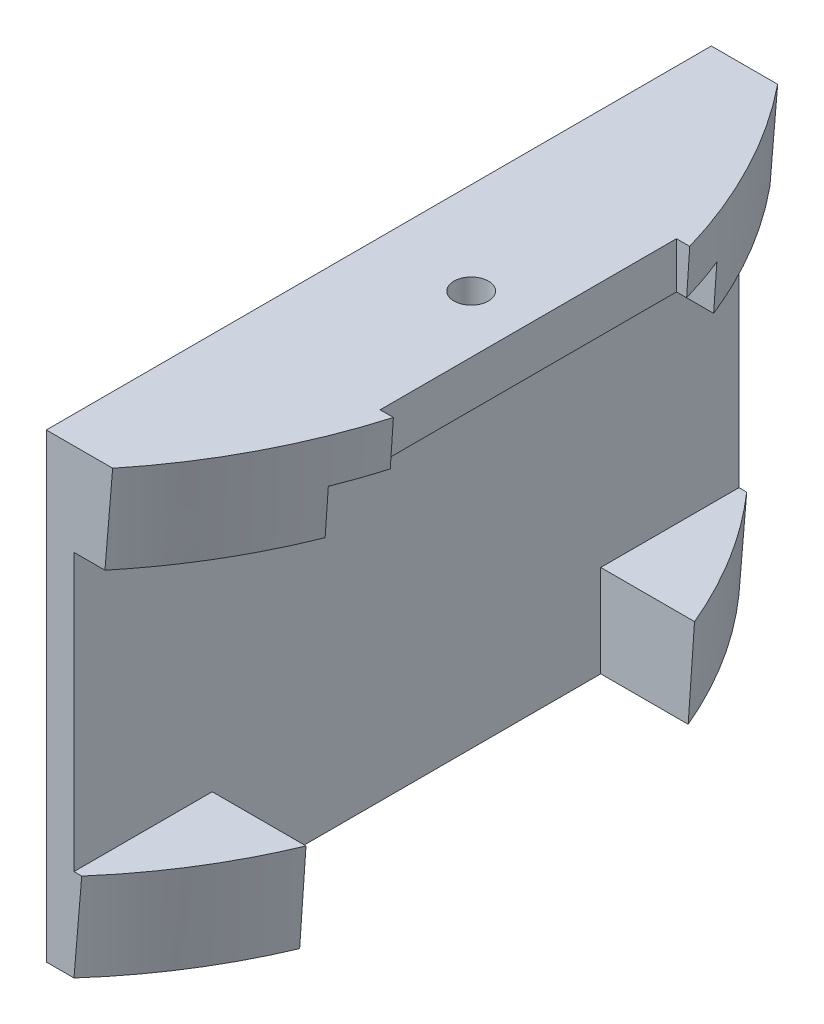
SolidWorks part; units mm, degrees
other "Markup1"
sketch "Sketch9" plane through (70.0388, 63.5001, -45.8198) normal (0.0909, 0.7926, -0.603) x (-0.9958, 0.0771, -0.0488)
ref_plane "Front Plane" through (0, 0, 0) normal (0, 0, 1) x (1, 0, 0)
ref_plane "Top Plane" through (0, 0, 0) normal (0, 1, 0) x (1, 0, 0)
ref_plane "Right Plane" through (0, 0, 0) normal (1, 0, 0) x (0, 0, -1)
sketch "Sketch1" plane through (0, 0, 0) normal (0, 1, 0) x (1, 0, 0)
  line L1 (47.5581, 45.8197) -> (47.5581, -45.8197)
  line L2 (47.5581, 45.8197) -> (51.3681, 45.8197)
  line L3 (47.5581, -45.8197) -> (51.3681, -45.8197)
  arc A0 (51.3681, -45.8197) -> (51.3681, 45.8197) centre (0, 0) ccw
  dimension "D1" = 137.668
ref_plane "Plane1" through (0, 63.5, 0) normal (0, 1, 0) x (1, 0, 0)
sketch "Sketch2" plane through (0, 63.5, 0) normal (0, 1, 0) x (1, 0, 0)
  line L0 (47.5581, 45.8197) -> (47.5581, -45.8197) construction
  line L1 (47.5581, 45.8197) -> (47.5581, -45.8197)
  line L2 (47.5581, 45.8197) -> (56.6981, 45.8197)
  line L3 (47.5581, -45.8197) -> (56.6981, -45.8197)
  arc A0 (56.6981, -45.8197) -> (56.6981, 45.8197) centre (0, 0) ccw
  dimension "D1" = 145.796
loft "Loft1" add profiles "Sketch1", "Sketch2"
sketch "Sketch5" plane through (0, 0, 0) normal (0, -1, 0) x (1, 0, 0)
  line L0 (63.4153, 26.7697) -> (102.9917, 26.7697)
  line L1 (51.3681, 26.7697) -> (63.4153, 26.7697)
  line L2 (102.9917, 26.7697) -> (102.9917, -26.7697)
  line L3 (51.3681, 45.8197) -> (47.5581, 45.8197)
  line L4 (47.5581, 45.8197) -> (47.5581, -45.8197)
  line L5 (47.5581, -45.8197) -> (51.3681, -45.8197)
  line L6 (51.3681, 45.8197) -> (47.5581, 45.8197)
  line L8 (47.5581, -45.8197) -> (51.3681, -45.8197)
  line L9 (51.3681, -26.7697) -> (63.4153, -26.7697)
  line L10 (51.3681, 26.7697) -> (51.3681, -26.7697)
  line L11 (102.9917, -26.7697) -> (63.4153, -26.7697)
  arc A1 (51.3681, -45.8197) -> (51.3681, 45.8197) centre (0, 0) ccw
  dimension "D2" = 19.05
  dimension "D3" = 19.05
  dimension "D1" = 0
extrude "Cut-Extrude1" cut sketch "Sketch5" against normal blind 57.15
sketch "Sketch6" plane through (0, 63.5, 0) normal (0, 1, 0) x (1, 0, 0)
  line L0 (56.6981, 45.8197) -> (56.6981, 20.4197)
  line L1 (56.6981, 20.4197) -> (69.9797, 20.4197)
  line L2 (56.6981, -45.8197) -> (56.6981, -20.4197)
  line L3 (56.6981, -20.4197) -> (69.9797, -20.4197)
  line L5 (68.1525, 20.4197) -> (103.7378, 20.4197)
  line L6 (68.1525, 20.4197) -> (68.1525, -20.4197)
  line L7 (68.1525, -20.4197) -> (103.7378, -20.4197)
  line L8 (103.7378, 20.4197) -> (103.7378, -20.4197)
  arc A0 (56.6981, -45.8197) -> (56.6981, 45.8197) centre (0, 0) ccw construction
  dimension "D1" = 25.4
  dimension "D2" = 25.4
extrude "Cut-Extrude2" cut sketch "Sketch6" against normal blind 57.15
sketch "Sketch7" plane through (0, 0, 0) normal (0, 0, 1) x (1, 0, 0)
  line L0 (12.3645, 63.5) -> (-12.3645, 63.5) construction
  line L1 (51.3681, 12.7) -> (95.2503, 12.7)
  line L2 (51.3681, 12.7) -> (51.3681, 50.8)
  line L3 (51.3681, 50.8) -> (95.2503, 50.8)
  line L4 (95.2503, 12.7) -> (95.2503, 50.8)
  line L5 (47.5581, 0) -> (51.3681, 0) construction
  line L6 (47.5581, 0) -> (47.5581, 63.5) construction
  dimension "D1" = 12.7
  dimension "D2" = 12.7
  dimension "D3" = 3.81
extrude "Cut-Extrude3" cut sketch "Sketch7" against normal through all both and the other way through all
sketch "Sketch8" plane through (0, 57.15, 0) normal (0, -1, 0) x (1, 0, 0)
  line L2 (51.3681, 26.7697) -> (67.365, 26.7697) construction
  line L4 (51.3681, 26.7697) -> (51.3681, -26.7697) construction
  circle A0 centre (60.2581, -0.0273) radius 2.3813
  dimension "D1" = 4.7625
  dimension "D2" = 26.797
  dimension "D3" = 8.89
extrude "Cut-Extrude4" cut sketch "Sketch8" against normal blind 57.15
